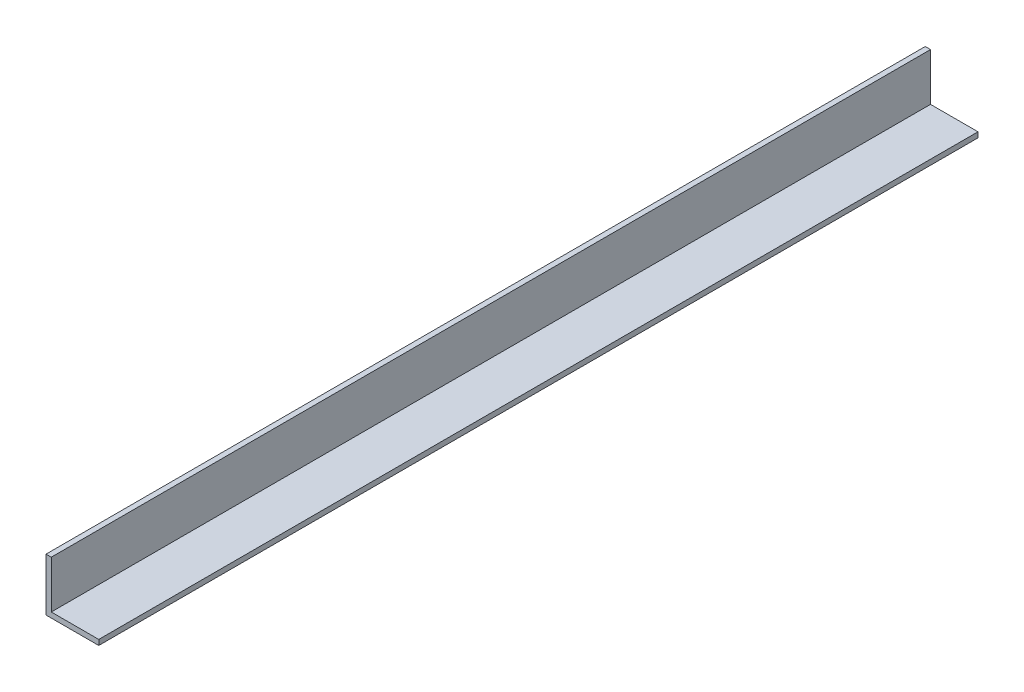
SolidWorks part; units mm, degrees
ref_plane "Front Plane" through (0, 0, 0) normal (0, 0, 1) x (1, 0, 0)
ref_plane "Top Plane" through (0, 0, 0) normal (0, 1, 0) x (1, 0, 0)
ref_plane "Right Plane" through (0, 0, 0) normal (1, 0, 0) x (0, 0, -1)
sketch "Sketch1" plane through (0, 0, 0) normal (0, 0, 1) x (1, 0, 0)
  line L0 (0, 0) -> (0, 30)
  line L1 (0, 30) -> (3, 30)
  line L2 (3, 30) -> (3, 3)
  line L3 (3, 3) -> (30, 3)
  line L4 (30, 3) -> (30, 0)
  line L5 (30, 0) -> (0, 0)
  dimension "D1" = 30
  dimension "D2" = 30
  dimension "D3" = 3
  dimension "D4" = 3
extrude "Boss-Extrude1" add sketch "Sketch1" along normal blind 500
